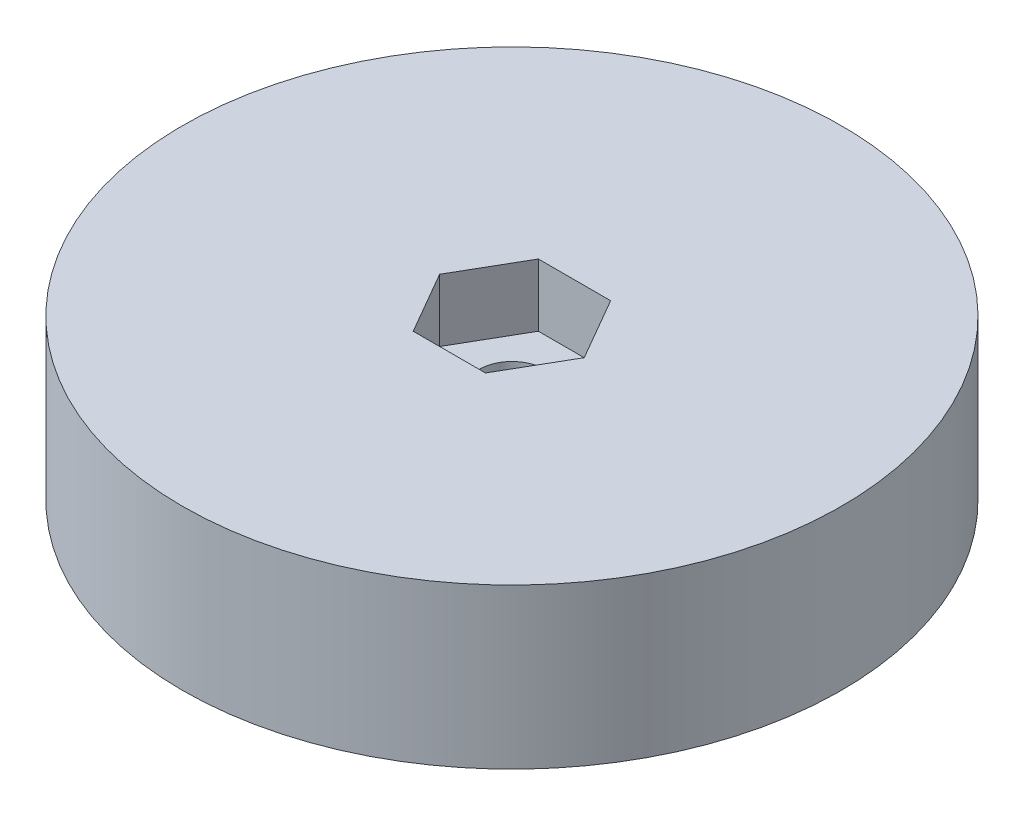
SolidWorks part; units mm, degrees
ref_plane "Front Plane" through (0, 0, 0) normal (0, 0, 1) x (1, 0, 0)
ref_plane "Top Plane" through (0, 0, 0) normal (0, 1, 0) x (1, 0, 0)
ref_plane "Right Plane" through (0, 0, 0) normal (1, 0, 0) x (0, 0, -1)
sketch "Sketch1" plane through (0, 0, 0) normal (0, 1, 0) x (1, 0, 0)
  line L0 (0, 0) -> (0, 24)
  line L1 (0, 24) -> (9.75, 24)
  line L2 (9.75, 24) -> (9.75, 34)
  line L3 (0, 0) -> (24, 0)
  line L4 (24, 0) -> (24, 24)
  line L5 (24, 24) -> (14.25, 24)
  line L6 (14.25, 24) -> (14.25, 34)
  line L7 (0, 12) -> (24, 12) construction
  line L9 (9.75, 28.5) -> (14.25, 28.5)
  arc A2 (14.25, 34) -> (9.75, 34) centre (12, 12) cw
  arc A3 (22.5, 24) -> (24, 22.5) centre (24, 24) cw
  arc A4 (24, 1.5) -> (22.5, 0) centre (24, 0) cw
  arc A5 (1.5, 0) -> (0, 1.5) centre (0, 0) cw
  arc A6 (1.5, 24) -> (0, 22.5) centre (0, 24) ccw
  arc A7 (14.25, 34) -> (9.75, 34) centre (12, 12) ccw
  dimension "D1" = 24
  dimension "D7" = 1.5
  dimension "D5" = 1.5
  dimension "D8" = 1.5
  dimension "D9" = 1.5
  dimension "D2" = 24
  dimension "D3" = 4.5
  dimension "D4" = 10
  dimension "D6" = 4.5
extrude "Boss-Extrude1" add sketch "Sketch1" along normal blind 5.5
fillet "Fillet1" radius 2 8 edges at (22.5, 2.75, 0) (24, 2.75, -1.5) (24, 2.75, -22.5) (0, 2.75, -1.5) (1.5, 2.75, 0) (0, 2.75, -22.5) (22.5, 2.75, -24) (1.5, 2.75, -24)
sketch "Sketch2" plane through (0, 5.5, 0) normal (0, 1, 0) x (1, 0, 0)
  circle A0 centre (12, 12) radius 22.1148
  circle A1 centre (12, 12) radius 22.1148 construction
extrude "Boss-Extrude2" add sketch "Sketch2" along normal blind 5.2
sketch "Sketch3" plane through (0, 10.7, 0) normal (0, 1, 0) x (1, 0, 0)
  line L0 (-10.1148, 12) -> (34.1148, 12) construction
  line L2 (16.8497, 12) -> (14.4249, 16.2)
  line L3 (14.4249, 16.2) -> (9.5751, 16.2)
  line L4 (9.5751, 16.2) -> (7.1503, 12)
  line L5 (7.1503, 12) -> (9.5751, 7.8)
  line L6 (9.5751, 7.8) -> (14.4249, 7.8)
  line L7 (14.4249, 7.8) -> (16.8497, 12)
  circle A0 centre (12, 12) radius 22.1148 construction
  circle A1 centre (12, 12) radius 4.2 construction
  point P6 (12.6421, 7.193)
  point P14 (0, 0)
  dimension "D1" = 8.4
extrude "Cut-Extrude1" cut sketch "Sketch3" against normal blind 4.2
sketch "Sketch4" plane through (0, 6.5, 0) normal (0, 1, 0) x (1, 0, 0)
  circle A0 centre (12, 12) radius 2.2
  circle A1 centre (12, 12) radius 22.1148 construction
  dimension "D1" = 4.4
extrude "Cut-Extrude2" cut sketch "Sketch4" against normal blind 4.2
